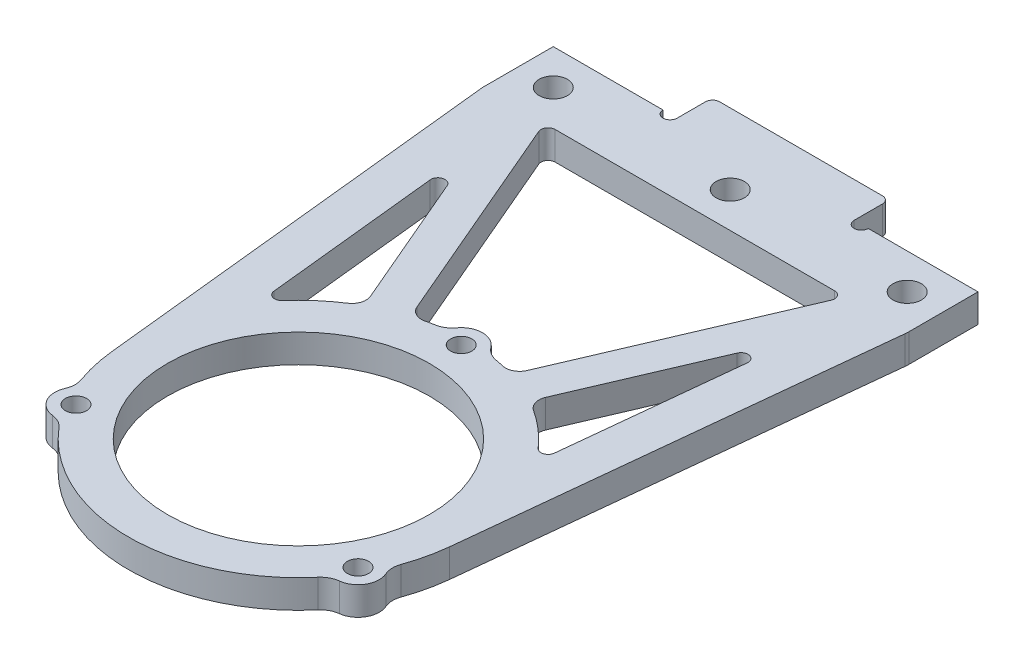
SolidWorks part; units mm, degrees
material "Thornel Mat VMA"
ref_plane "前视基准面" through (0, 0, 0) normal (0, 0, 1) x (1, 0, 0)
ref_plane "上视基准面" through (0, 0, 0) normal (0, 1, 0) x (1, 0, 0)
ref_plane "右视基准面" through (0, 0, 0) normal (1, 0, 0) x (0, 0, -1)
sketch "草图1" plane through (0, 0, 0) normal (0, 1, 0) x (1, 0, 0)
  line L0 (-23.8693, -2.5014) -> (-31.048, 66)
  line L1 (-31.048, 66) -> (31.048, 66)
  line L2 (31.048, 66) -> (23.8693, -2.5014)
  line L3 (0, 0) -> (0, 66) construction
  line L5 (-30, 56) -> (30, 56) construction
  line L6 (-30, 56) -> (-30, 66) construction
  line L7 (-30, 66) -> (30, 66) construction
  line L8 (30, 56) -> (30, 66) construction
  line L9 (-30, 56) -> (30, 66) construction
  line L10 (-30, 66) -> (30, 56) construction
  circle A0 centre (0, 0) radius 18.5
  circle A1 centre (0, 0) radius 24
  point P6 (32.4747, 56)
  point P9 (29.1054, 56)
  point P11 (0, 61)
  dimension "D1" = 48
  dimension "D2" = 37
  dimension "D3" = 66
  dimension "D4" = 10
  dimension "D5" = 60
extrude "凸台-拉伸1" add sketch "草图1" along normal blind 4
sketch "草图2" plane through (0, 4, 0) normal (0, 1, 0) x (1, 0, 0)
  line L0 (0, 0) -> (0, -31.5) construction
  circle A0 centre (0, -31.5) radius 5
  circle A1 centre (0, 0) radius 23 construction
  circle A2 centre (0, 23) radius 1.5
  circle A3 centre (19.9186, -11.5) radius 1.5
  circle A4 centre (-19.9186, -11.5) radius 1.5
  point P13 (0, 0)
  dimension "D2" = 10
  dimension "D3" = 46
  dimension "D4" = 3
  dimension "D1" = 31.5
  dimension "D5" = 3
extrude "切除-拉伸1" cut sketch "草图2" against normal blind 10
fillet "圆角1" [suppressed] radius 5
sketch "草图4" plane through (0, 4, 0) normal (0, 1, 0) x (1, 0, 0)
  line L0 (-30.524, 61) -> (30.524, 61) construction
  line L1 (-23.8693, -2.5014) -> (-31.048, 66) construction
  line L2 (31.048, 66) -> (23.8693, -2.5014) construction
  line L3 (-31.048, 66) -> (31.048, 66) construction
  circle A0 centre (-25, 61) radius 2
  circle A1 centre (0, 61) radius 2
  circle A2 centre (25, 61) radius 2
  dimension "D2" = 25
  dimension "D3" = 4
  dimension "D1" = 5
  dimension "D4" = 3
extrude "切除-拉伸2" cut sketch "草图4" against normal blind 4
sketch "草图5" plane through (0, 4, 0) normal (0, 1, 0) x (1, 0, 0)
  line L0 (0, 0) -> (0, 68.5) construction
  line L1 (-31.048, 66) -> (31.048, 66) construction
  line L2 (-12.5, 71) -> (12.5, 71)
  line L3 (-12.5, 71) -> (-12.5, 66)
  line L4 (-12.5, 66) -> (12.5, 66)
  line L5 (12.5, 71) -> (12.5, 66)
  line L6 (-12.5, 71) -> (12.5, 66) construction
  line L7 (-12.5, 66) -> (12.5, 71) construction
  dimension "D1" = 5
  dimension "D2" = 25
extrude "凸台-拉伸2" add sketch "草图5" against normal blind 4
sketch "草图6" plane through (0, 4, 0) normal (0, 1, 0) x (1, 0, 0)
  line L0 (-31.048, 66) -> (-12.5, 66) construction
  line L1 (12.5, 66) -> (31.048, 66) construction
  circle A0 centre (-13.5, 66) radius 1
  circle A1 centre (13.5, 66) radius 1
  dimension "D1" = 2
extrude "切除-拉伸3" cut sketch "草图6" against normal blind 10
fillet "圆角2" radius 1 2 edges at (-12.5, 2, -71) (12.5, 2, -71)
sketch "草图7" plane through (0, 4, 0) normal (0, 1, 0) x (1, 0, 0)
  line L0 (-19.5565, 13.912) -> (-23.9671, 56)
  line L1 (-23.9671, 56) -> (23.9671, 56)
  line L2 (23.9671, 56) -> (19.5565, 13.912)
  line L4 (14.5, 66) -> (31.048, 66) construction
  line L5 (31.048, 66) -> (23.8693, -2.5014) construction
  line L6 (-23.8693, -2.5014) -> (-31.048, 66) construction
  arc A0 (19.5565, 13.912) -> (2.884, 23.8261) centre (0, 0) ccw
  arc A1 (2.884, 23.8261) -> (-2.884, 23.8261) centre (0, 23) ccw
  arc A2 (-2.884, 23.8261) -> (-19.5565, 13.912) centre (0, 0) ccw
  point P9 (22.9668, 8.5309)
  point P11 (0, 0)
  point P16 (0, 0)
  dimension "D1" = 48
  dimension "D4" = 6
  dimension "D2" = 6
  dimension "D3" = 10
  dimension "D5" = 6
extrude "切除-拉伸4" cut sketch "草图7" against normal blind 5
sketch "草图8" plane through (0, 4, 0) normal (0, 1, 0) x (1, 0, 0)
  line L0 (-23.9671, 56) -> (-7.2791, 17.0078)
  line L1 (23.9671, 56) -> (7.2791, 17.0078)
  circle A1 centre (0, 0) radius 18.5 construction
extrude "拉伸-薄壁1" add sketch "草图8" against normal blind 4 thin thin type mid plane wall 5
fillet "圆角3" radius 2 4 edges at (7.0934, 2, -22.9278) (-7.0934, 2, -22.9278) (-11.6901, 2, -20.9605) (11.6901, 2, -20.9605)
fillet "圆角4" radius 3 2 edges at (-2.884, 2, -23.8261) (2.884, 2, -23.8261)
fillet "圆角5" radius 1 6 edges at (-19.5565, 2, -13.912) (19.5565, 2, -13.912) (23.0854, 2, -47.5859) (21.2478, 2, -56) (-21.2478, 2, -56) (-23.0854, 2, -47.5859)
sketch "草图10" plane through (0, 4, 0) normal (0, 1, 0) x (1, 0, 0)
  circle A0 centre (-19.9186, -11.5) radius 3
  circle A1 centre (-19.9186, -11.5) radius 1.5
  circle A2 centre (19.9186, -11.5) radius 1.5
  circle A3 centre (19.9186, -11.5) radius 3
  arc A4 (2.4129, 24.7826) -> (-2.4129, 24.7826) centre (0, 23) ccw construction
extrude "凸台-拉伸3" add sketch "草图10" against normal blind 4
fillet "圆角6" radius 3 4 edges at (19.192, 2, 14.4107) (22.076, 2, 9.4154) (-19.192, 2, 14.4107) (-22.076, 2, 9.4154)
sketch "草图11" plane through (0, 4, 0) normal (0, 1, 0) x (1, 0, 0)
  line L0 (-30, 66) -> (-30, 56)
  line L1 (-31.048, 66) -> (-14.5, 66) construction
  line L2 (-23.8693, -2.5014) -> (-31.048, 66) construction
  line L3 (-30, 66) -> (-31.048, 66)
  line L4 (-31.048, 66) -> (-30, 56)
  line L5 (0, -2.2) -> (0, 2.2) construction
  line L6 (30, 66) -> (31.048, 66)
  line L7 (30, 66) -> (30, 56)
  line L8 (31.048, 66) -> (30, 56)
  circle A0 centre (-25, 61) radius 2 construction
  dimension "D1" = 5
extrude "切除-拉伸5" cut sketch "草图11" against normal blind 4
fillet "圆角7" radius 5 2 edges at (30, 2, -56) (-30, 2, -56)
